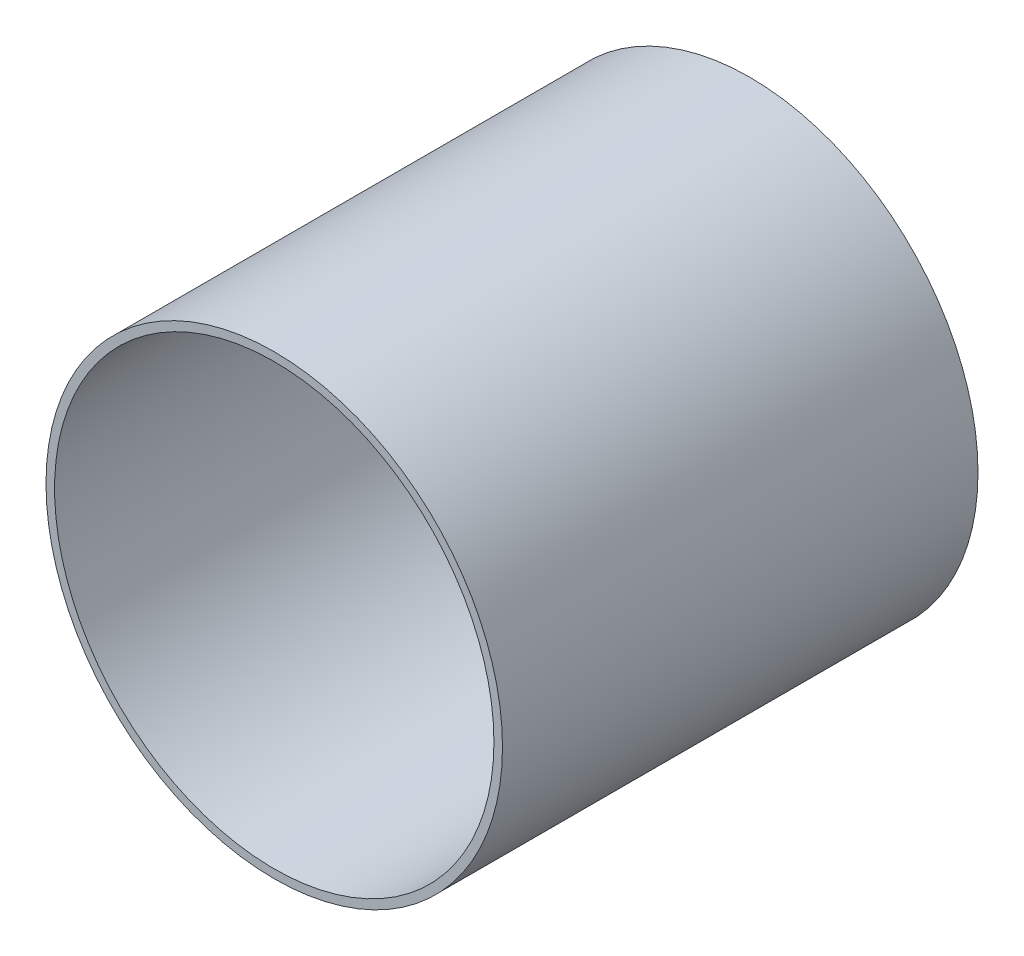
SolidWorks part; units mm, degrees
ref_plane "Front Plane" through (0, 0, 0) normal (0, 0, 1) x (1, 0, 0)
ref_plane "Top Plane" through (0, 0, 0) normal (0, 1, 0) x (1, 0, 0)
ref_plane "Right Plane" through (0, 0, 0) normal (1, 0, 0) x (0, 0, -1)
sketch "Sketch1" plane through (0, 0, 0) normal (0, 0, 1) x (1, 0, 0)
  circle A0 centre (0, 0) radius 11.55
  circle A1 centre (0, 0) radius 12
  dimension "D1" = 24
  dimension "D2" = 23.1
extrude "Boss-Extrude1" add sketch "Sketch1" along normal blind 25
